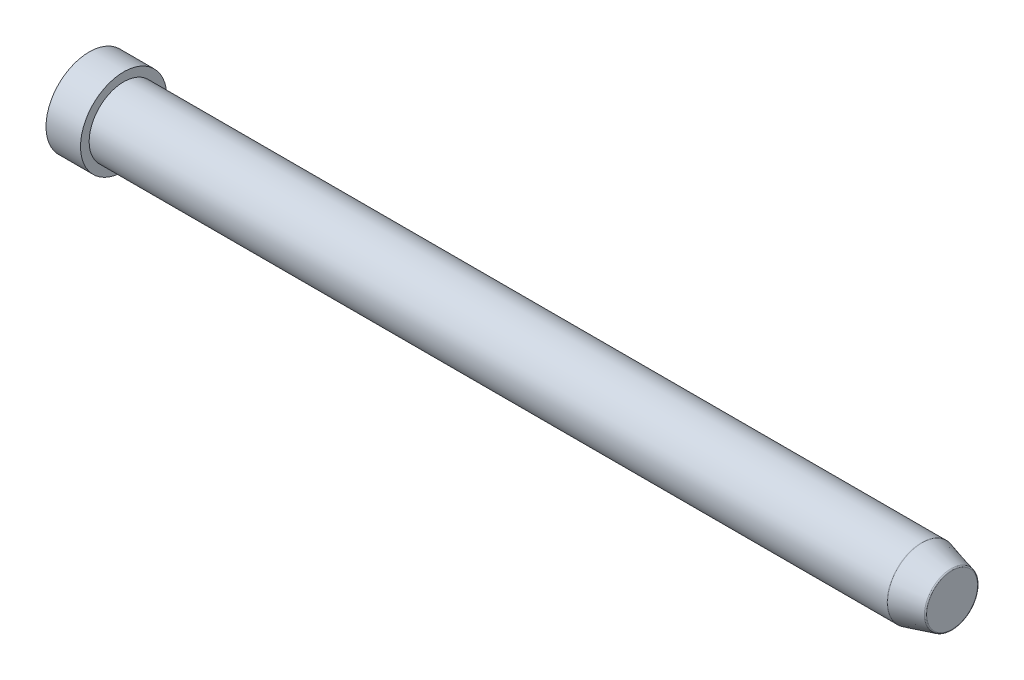
SolidWorks part; units mm, degrees
material "Brass"
ref_plane "Front Plane" through (0, 0, 0) normal (0, 0, 1) x (1, 0, 0)
ref_plane "Top Plane" through (0, 0, 0) normal (0, 1, 0) x (1, 0, 0)
ref_plane "Right Plane" through (0, 0, 0) normal (1, 0, 0) x (0, 0, -1)
sketch "Sketch1" plane through (0, 0, 0) normal (0, 0, 1) x (1, 0, 0)
  line L0 (0, 0) -> (200, 0)
  line L1 (8, 10) -> (8, 8)
  line L2 (0, 0) -> (0, 10)
  line L3 (0, 10) -> (8, 10)
  line L4 (8, 8) -> (200, 8)
  line L5 (200, 8) -> (200, 0)
revolve "Revolve1" add sketch "Sketch1" angle 360 about L0
chamfer "Chamfer1" distance 7 angle 15 1 edges at (200, 0, 8)
fillet "Fillet1" radius 0.3 2 edges at (193, 0, 8) (200, 0, 6.1244)
